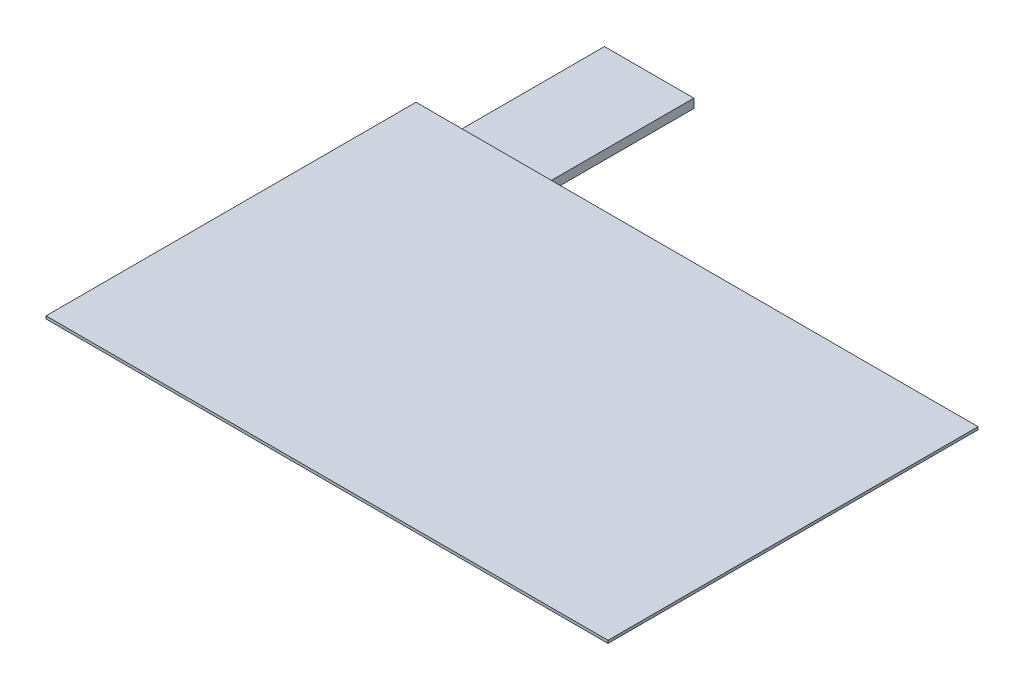
SolidWorks part; units mm, degrees
material "Pure Gold"
ref_plane "Front Plane" through (0, 0, 0) normal (0, 0, 1) x (1, 0, 0)
ref_plane "Top Plane" through (0, 0, 0) normal (0, 1, 0) x (1, 0, 0)
ref_plane "Right Plane" through (0, 0, 0) normal (1, 0, 0) x (0, 0, -1)
sketch "Sketch1" plane through (0, 0, 0) normal (0, 1, 0) x (1, 0, 0)
  line L1 (-127.7938, -84.1375) -> (127.7937, -84.1375)
  line L2 (-127.7938, -84.1375) -> (-127.7938, 84.1375)
  line L3 (-127.7938, 84.1375) -> (127.7937, 84.1375)
  line L4 (127.7937, -84.1375) -> (127.7937, 84.1375)
  line L5 (-127.7938, -84.1375) -> (127.7937, 84.1375) construction
  line L6 (-127.7938, 84.1375) -> (127.7937, -84.1375) construction
  point P0 (0, 0)
  dimension "D1" = 168.275
  dimension "D2" = 255.5875
extrude "Boss-Extrude1" add sketch "Sketch1" along normal blind 1.2446
sketch "Sketch2" plane through (0, 0, 0) normal (0, -1, 0) x (1, 0, 0)
  line L1 (-114.3, -68.2625) -> (114.3, -68.2625)
  line L2 (-114.3, -68.2625) -> (-114.3, 68.2625)
  line L3 (-114.3, 68.2625) -> (114.3, 68.2625)
  line L4 (114.3, -68.2625) -> (114.3, 68.2625)
  line L5 (-114.3, -68.2625) -> (114.3, 68.2625) construction
  line L6 (-114.3, 68.2625) -> (114.3, -68.2625) construction
  point P0 (0, 0)
  dimension "D1" = 228.6
  dimension "D2" = 136.525
extrude "Boss-Extrude2" add sketch "Sketch2" along normal blind 4.0894
sketch "Sketch3" plane through (0, -4.0894, 0) normal (0, -1, 0) x (1, 0, 0)
  line L0 (-127.7938, -84.1375) -> (-127.7938, 84.1375) construction
  line L1 (-108.1088, -68.2625) -> (-67.4688, -68.2625)
  line L2 (-108.1088, -68.2625) -> (-108.1088, -150.1775)
  line L3 (-108.1088, -150.1775) -> (-67.4688, -150.1775)
  line L4 (-67.4688, -68.2625) -> (-67.4688, -150.1775)
  line L5 (-108.1088, -68.2625) -> (-67.4688, -150.1775) construction
  line L6 (-108.1088, -150.1775) -> (-67.4688, -68.2625) construction
  line L7 (-127.7938, -84.1375) -> (-127.7938, 84.1375) construction
  line L8 (-114.3, -68.2625) -> (114.3, -68.2625) construction
  line L9 (127.7937, -84.1375) -> (-127.7938, -84.1375) construction
  point P0 (-87.7888, -109.22)
  dimension "D1" = 40.64
  dimension "D2" = 19.685
  dimension "D3" = 66.04
extrude "Cable" add sketch "Sketch3" against normal up to surface (4.0894 mm away) separate body up to face at (0, 0, 0)
